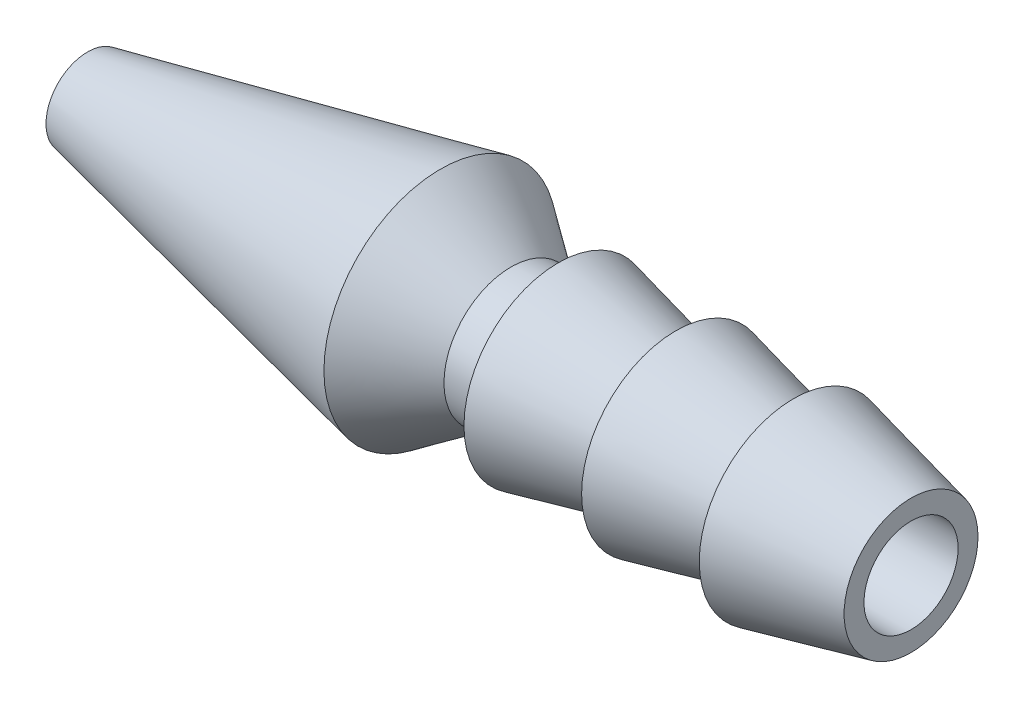
SolidWorks part; units mm, degrees
ref_plane "Front Plane" through (0, 0, 0) normal (0, 0, 1) x (1, 0, 0)
ref_plane "Top Plane" through (0, 0, 0) normal (0, 1, 0) x (1, 0, 0)
ref_plane "Right Plane" through (0, 0, 0) normal (1, 0, 0) x (0, 0, -1)
sketch "Sketch1" plane through (0, 0, 0) normal (1, 0, 0) x (0, 0, -1)
  circle A0 centre (0, 0) radius 4
extrude "Boss-Extrude1" add sketch "Sketch1" along normal blind 5 draft 13
sketch "Sketch2" plane through (5, 0, 0) normal (1, 0, 0) x (0, 0, -1)
  circle A0 centre (0, 0) radius 4
extrude "Boss-Extrude2" add sketch "Sketch2" along normal blind 5 draft 13
sketch "Sketch3" plane through (10, 0, 0) normal (1, 0, 0) x (0, 0, -1)
  circle A0 centre (0, 0) radius 4
extrude "Boss-Extrude3" add sketch "Sketch3" along normal blind 5 draft 13
sketch "Sketch4" plane through (0, 0, 0) normal (-1, 0, 0) x (0, 0, 1)
  circle A0 centre (0, 0) radius 2.85
extrude "Boss-Extrude4" add sketch "Sketch4" along normal blind 2
sketch "Sketch5" plane through (-2, 0, 0) normal (-1, 0, 0) x (0, 0, 1)
  circle A0 centre (0, 0) radius 2.85
extrude "Boss-Extrude5" add sketch "Sketch5" along normal blind 3 draft 35 draft outward yes
sketch "Sketch6" plane through (-5, 0, 0) normal (-1, 0, 0) x (0, 0, 1)
  circle A0 centre (0, 0) radius 4.9506
extrude "Boss-Extrude6" add sketch "Sketch6" along normal blind 15 draft 12
sketch "Sketch9" plane through (15, 0, 0) normal (1, 0, 0) x (0, 0, -1)
  circle A0 centre (0, 0) radius 2
extrude "Cut-Extrude1" cut sketch "Sketch9" against normal blind 20
sketch "Sketch11" plane through (-20, 0, 0) normal (-1, 0, 0) x (0, 0, 1)
  circle A0 centre (0, 0) radius 1.25
extrude "Cut-Extrude5" cut sketch "Sketch11" against normal blind 15 draft 2.8 contours A0 draft outward yes
